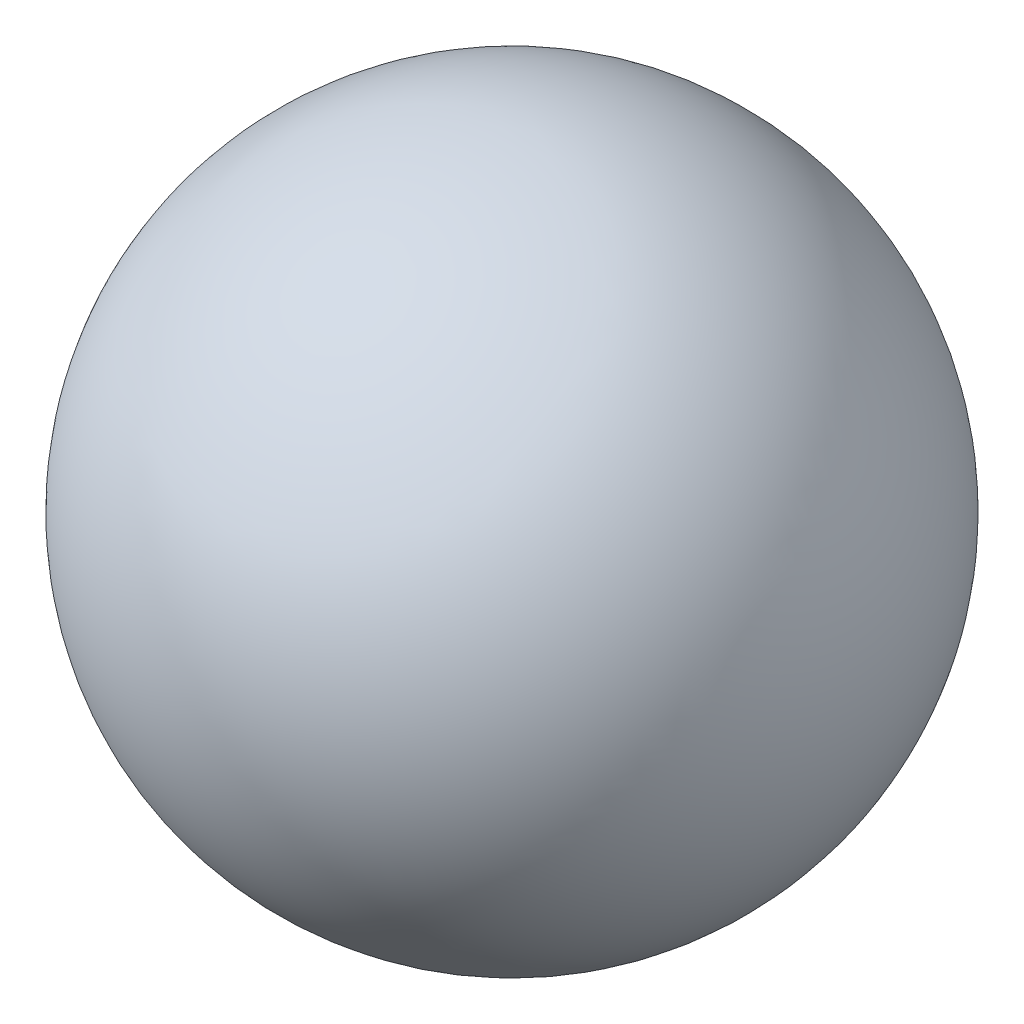
SolidWorks part; units mm, degrees
ref_plane "Front Plane" through (0, 0, 0) normal (0, 0, 1) x (1, 0, 0)
ref_plane "Top Plane" through (0, 0, 0) normal (0, 1, 0) x (1, 0, 0)
ref_plane "Right Plane" through (0, 0, 0) normal (1, 0, 0) x (0, 0, -1)
sketch "SEmiCircleSketch1" plane through (0, 0, 0) normal (0, 1, 0) x (1, 0, 0)
  line L0 (0, 0) -> (0, 25)
  arc A0 (0, 0) -> (0, 25) centre (0, 12.5) cw
  point P4 (-12.5, 12.5)
  dimension "D1" = 25
  dimension "D2" = 12.5
revolve "Revolve1" add sketch "SEmiCircleSketch1" angle 360 about L0
sketch "Sketch2" plane through (0, 0, 0) normal (1, 0, 0) x (0, 0, -1)
  circle A0 centre (12.5, 0) radius 2
  circle A1 centre (12.5, 0) radius 12.5 construction
  dimension "D1" = 4
extrude "Cut-Extrude1" cut sketch "Sketch2" against normal blind 12.5
equation "\"BallJointDiameter\"=25"
equation "\"D1@SEmiCircleSketch1\" = \"BallJointDiameter\""
equation "\"D2@SEmiCircleSketch1\" = \"BallJointDiameter\" / 2"
equation "\"M4ScrewDiameter\"=4"
equation "\"D1@Sketch2\"=\"M4ScrewDiameter\""
equation "\"D1@Cut-Extrude1\"=\"BallJointDiameter\"/2"
